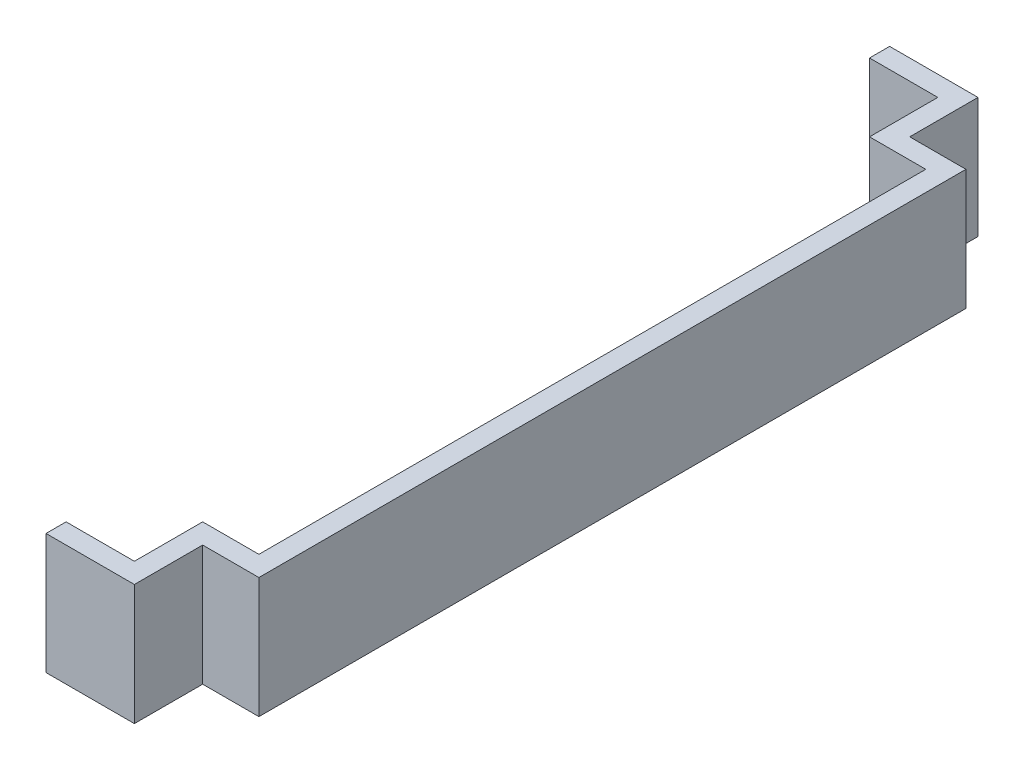
SolidWorks part; units mm, degrees
ref_plane "Front Plane" through (0, 0, 0) normal (0, 0, 1) x (1, 0, 0)
ref_plane "Top Plane" through (0, 0, 0) normal (0, 1, 0) x (1, 0, 0)
ref_plane "Right Plane" through (0, 0, 0) normal (1, 0, 0) x (0, 0, -1)
sketch "Sketch1" plane through (0, 0, 0) normal (0, 1, 0) x (1, 0, 0)
  line L0 (0, 0) -> (2.5, 0) construction
  line L1 (2.5, 44) -> (2.5, -44)
  line L2 (2.5, -44) -> (-4.5, -44)
  line L3 (-4.5, -44) -> (-4.5, -52.5)
  line L4 (-4.5, -52.5) -> (-15.5, -52.5)
  line L5 (0, -41.5) -> (-7, -41.5)
  line L6 (-7, -41.5) -> (-7, -50)
  line L7 (0, -41.5) -> (0, 41.5)
  line L8 (-7, -50) -> (-15.5, -50)
  line L9 (-15.5, -50) -> (-15.5, -52.5)
  line L10 (-15.5, 50) -> (-15.5, 52.5)
  line L11 (-7, 50) -> (-15.5, 50)
  line L12 (-7, 41.5) -> (-7, 50)
  line L13 (0, 41.5) -> (-7, 41.5)
  line L14 (-4.5, 52.5) -> (-15.5, 52.5)
  line L15 (-4.5, 44) -> (-4.5, 52.5)
  line L16 (2.5, 44) -> (-4.5, 44)
  dimension "D1" = 8.5
  dimension "D2" = 83
  dimension "D3" = 7
  dimension "D4" = 2.5
  dimension "D5" = 2.5
  dimension "D6" = 2.5
  dimension "D7" = 2.5
extrude "Boss-Extrude1" add sketch "Sketch1" along normal blind 15
sketch "Sketch2" plane through (0, 0, 0) normal (0, 0, 1) x (1, 0, 0)
  line L1 (-13.45, 3.3) -> (-13.45, 11.7) construction
  line L2 (-9.65, 11.7) -> (-9.65, 3.3) construction
  line L3 (-13.45, 3.3) -> (-13.45, 11.7) construction
  line L4 (-9.65, 11.7) -> (-9.65, 3.3) construction
  arc A0 (-9.65, 11.7) -> (-13.45, 11.7) centre (-11.55, 11.7) ccw construction
  arc A1 (-13.45, 3.3) -> (-9.65, 3.3) centre (-11.55, 3.3) ccw construction
  arc A2 (-9.65, 11.7) -> (-13.45, 11.7) centre (-11.55, 11.7) ccw construction
  arc A3 (-13.45, 3.3) -> (-9.65, 3.3) centre (-11.55, 3.3) ccw construction
